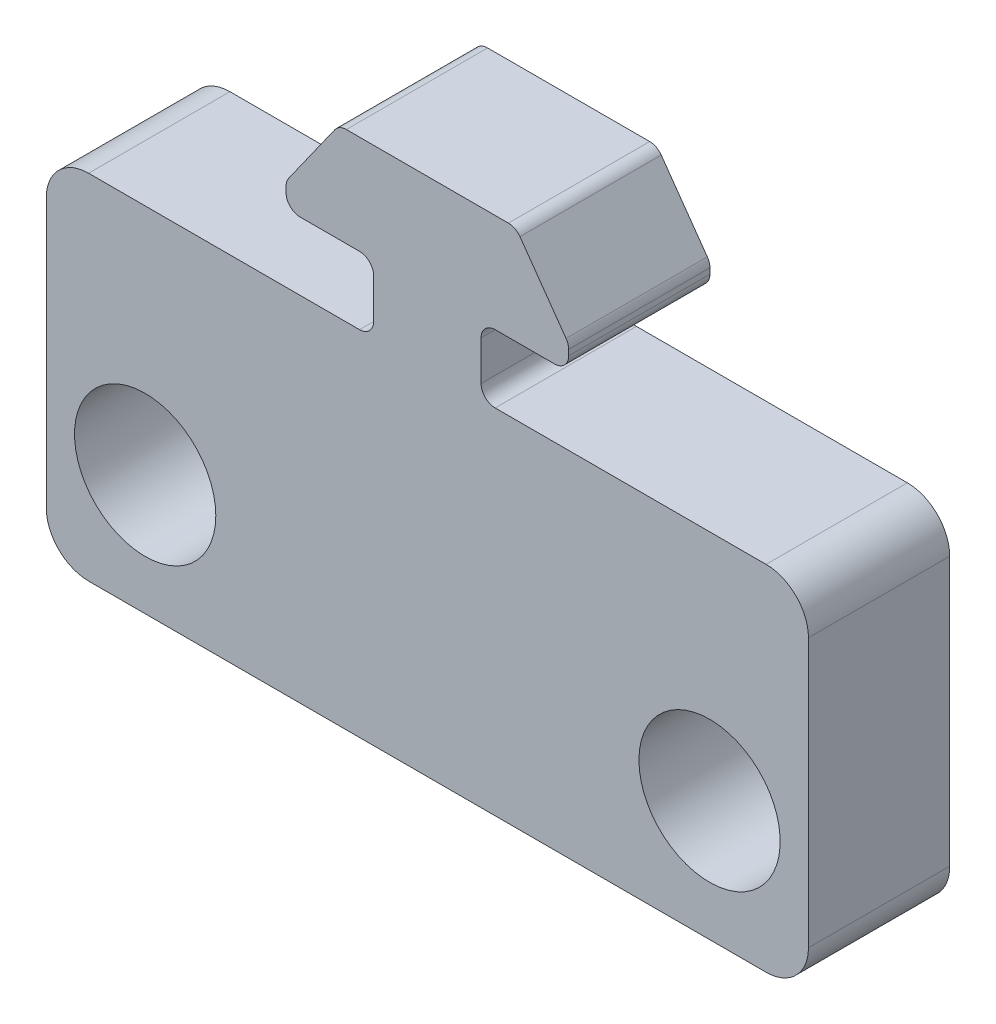
SolidWorks part; units mm, degrees
ref_plane "Front Plane" through (0, 0, 0) normal (0, 0, 1) x (1, 0, 0)
ref_plane "Top Plane" through (0, 0, 0) normal (0, 1, 0) x (1, 0, 0)
ref_plane "Right Plane" through (0, 0, 0) normal (1, 0, 0) x (0, 0, -1)
sketch "Sketch2" plane through (0, 0, 0) normal (0, 0, 1) x (1, 0, 0)
  line L0 (10, 0) -> (-10, 0)
  line L1 (-10, 0) -> (-10, 1.7099)
  line L2 (-10, 1.7099) -> (-6.2548, 7)
  line L3 (-6.2548, 7) -> (6.2548, 7)
  line L4 (0, 7) -> (0, 0)
  line L5 (0, 0) -> (0, 9.2516) construction
  line L6 (10, 1.7099) -> (6.2548, 7)
  line L7 (10, 0) -> (10, 1.7099)
  dimension "D1" = 20
  dimension "D2" = 7
extrude "Boss-Extrude1" add sketch "Sketch2" along normal blind 10 contours L4 L3 L2 L1 L0 | L0 L7 L6 L3 L4
sketch "Sketch4" plane through (0, 0, 0) normal (0, 0, 1) x (1, 0, 0)
  line L0 (-3.8, 0) -> (-3.8, -4.8)
  line L1 (10, 0) -> (-10, 0) construction
  line L2 (-3.8, -4.8) -> (-26.9734, -4.8)
  line L3 (-26.9734, -4.8) -> (-26.9734, -29.8)
  line L4 (-26.9734, -29.8) -> (26.9734, -29.8)
  line L5 (0, 0) -> (0, -29.8) construction
  line L6 (0, -29.8) -> (0, 0)
  line L7 (3.8, 0) -> (-3.8, 0)
  line L8 (0, 0) -> (0, -30.5381) construction
  line L9 (26.9734, -4.8) -> (26.9734, -29.8)
  line L10 (3.8, -4.8) -> (26.9734, -4.8)
  line L11 (3.8, 0) -> (3.8, -4.8)
  dimension "D1" = 4.8
  dimension "D2" = 3.8
  dimension "D3" = 25
extrude "Boss-Extrude2" add sketch "Sketch4" along normal blind 10 contours L6 L7 L0 L2 L3 L4 | L11 L7 L6 L4 L9 L10
sketch "Sketch5" plane through (0, 0, 0) normal (0, 0, 1) x (1, 0, 0)
  line L0 (-26.9734, -21.2886) -> (26.9734, -21.2886) construction
  line L3 (0, -29.8) -> (0, 7) construction
  line L4 (-26.9734, -29.8) -> (26.9734, -29.8) construction
  line L5 (-6.2548, 7) -> (6.2548, 7) construction
  circle A0 centre (-19.9734, -21.2886) radius 5
  circle A1 centre (19.9734, -21.2886) radius 5
  point P14 (-19.8643, -12.3)
  dimension "D1" = 7
extrude "Cut-Extrude1" cut sketch "Sketch5" along normal through all
fillet "Fillet1" radius 1 6 edges at (-10, 0, 5) (-10, 1.7099, 5) (-6.2548, 7, 5) (6.2548, 7, 5) (10, 0, 5) (10, 1.7099, 5)
fillet "Fillet2" radius 1 4 edges at (3.8, -4.8, 5) (3.8, 0, 5) (-3.8, -4.8, 5) (-3.8, 0, 5)
fillet "Fillet3" radius 3 4 edges at (-26.9734, -4.8, 5) (-26.9734, -29.8, 5) (26.9734, -4.8, 5) (26.9734, -29.8, 5)
